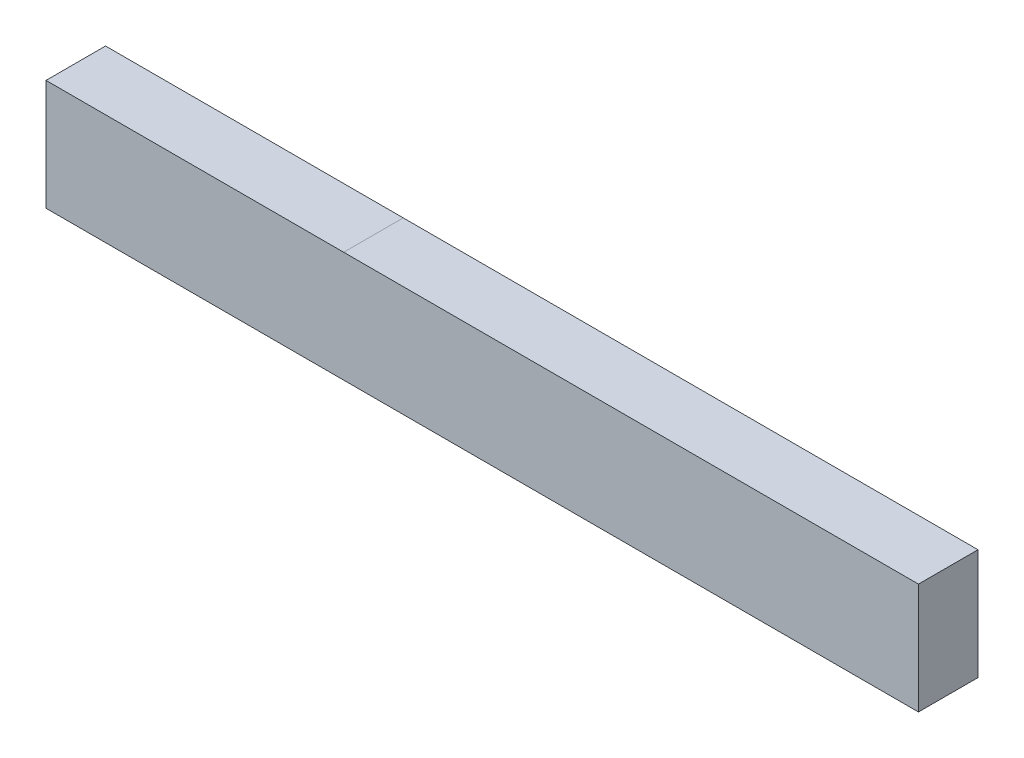
SolidWorks part; units mm, degrees
ref_plane "Płaszczyzna przednia" through (0, 0, 0) normal (0, 0, 1) x (1, 0, 0)
ref_plane "Płaszczyzna górna" through (0, 0, 0) normal (0, 1, 0) x (1, 0, 0)
ref_plane "Płaszczyzna prawa" through (0, 0, 0) normal (1, 0, 0) x (0, 0, -1)
sketch "Szkic1" plane through (0, 0, 0) normal (0, 0, 1) x (1, 0, 0)
  line L1 (0, 0) -> (146.5349, 0)
  line L2 (0, 0) -> (0, -18.6036)
  line L3 (0, -18.6036) -> (146.5349, -18.6036)
  line L4 (146.5349, 0) -> (146.5349, -18.6036)
extrude "Dodanie-wyciągnięcie1" add sketch "Szkic1" along normal blind 10
sketch "Szkic5" plane through (0, 0, 0) normal (0, 1, 0) x (1, 0, 0)
  line L0 (50, -10) -> (50, 0)
  line L1 (146.5349, -10) -> (0, -10) construction
  line L2 (146.5349, 0) -> (0, 0) construction
  line L3 (0, -10) -> (0, 0) construction
  point P8 (0, -5)
  dimension "D1" = 50
split line "Linia podziałowa2"
